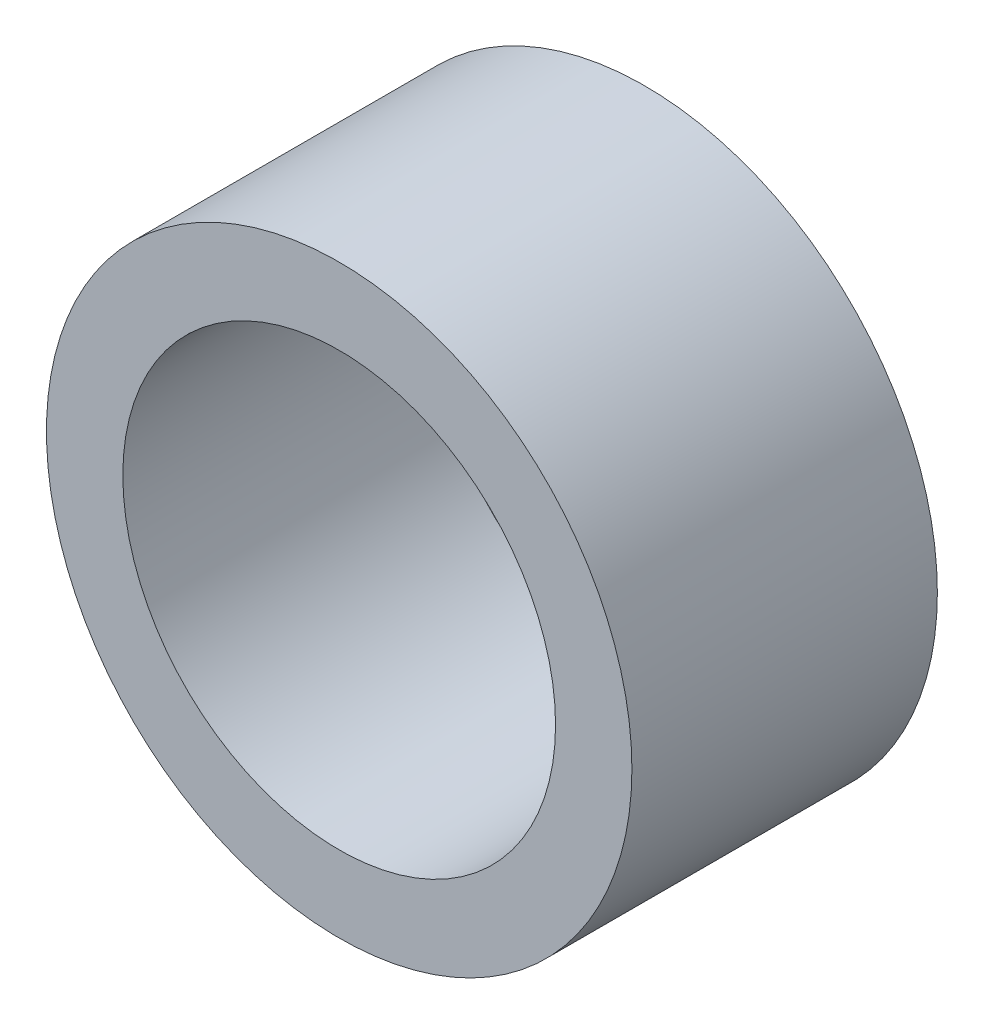
SolidWorks part; units mm, degrees
ref_plane "Спереди" through (0, 0, 0) normal (0, 0, 1) x (1, 0, 0)
ref_plane "Сверху" through (0, 0, 0) normal (0, 1, 0) x (1, 0, 0)
ref_plane "Справа" through (0, 0, 0) normal (1, 0, 0) x (0, 0, -1)
sketch "Эскиз1" plane through (0, 0, 0) normal (0, 0, 1) x (1, 0, 0)
  circle A0 centre (0, 0) radius 11.5
  circle A1 centre (0, 0) radius 8.5
extrude "Needle_bearing" add sketch "Эскиз1" along normal blind 12 from offset 40.5
